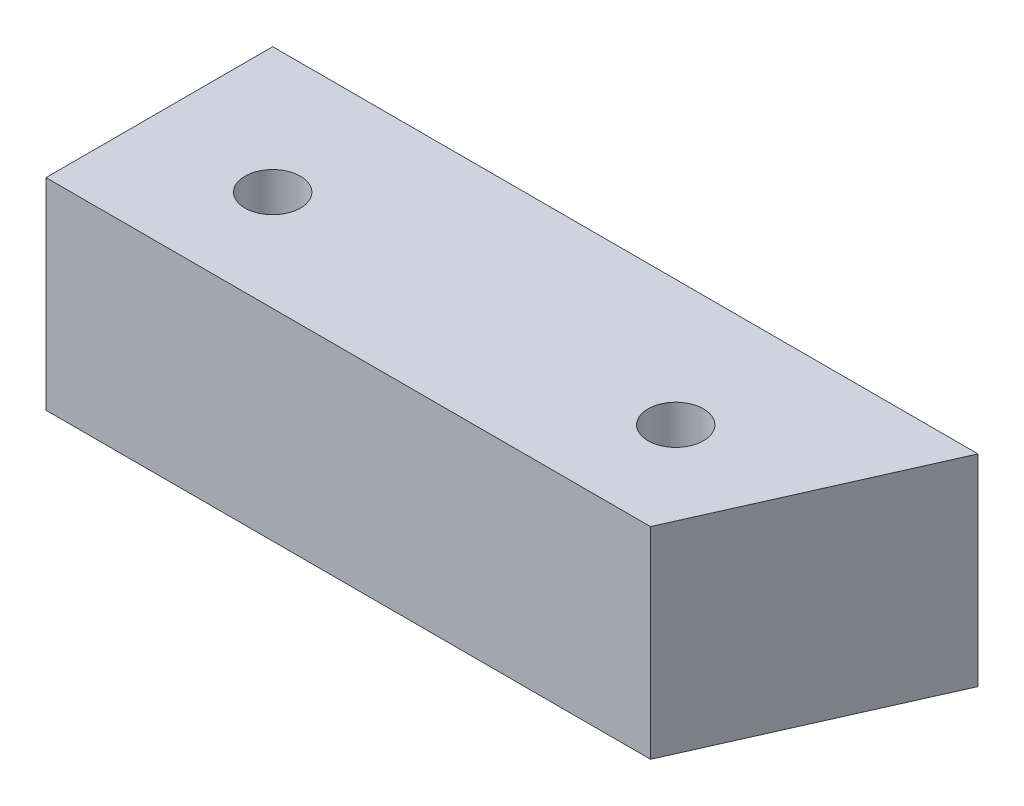
SolidWorks part; units mm, degrees
material "PA Type 6"
ref_plane "Front Plane" through (0, 0, 0) normal (0, 0, 1) x (1, 0, 0)
ref_plane "Top Plane" through (0, 0, 0) normal (0, 1, 0) x (1, 0, 0)
ref_plane "Right Plane" through (0, 0, 0) normal (1, 0, 0) x (0, 0, -1)
sketch "Sketch1" plane through (0, 0, 0) normal (0, 0, 1) x (1, 0, 0)
  line L1 (0, 0) -> (140, 0)
  line L2 (0, 0) -> (0, 40)
  line L3 (0, 40) -> (140, 40)
  line L4 (140, 0) -> (140, 40)
  dimension "D1" = 140
  dimension "D2" = 40
extrude "Boss-Extrude1" add sketch "Sketch1" along normal blind 45
sketch "Sketch2" plane through (0, 0, 0) normal (0, -1, 0) x (1, 0, 0)
  line L0 (120, 45) -> (140, 45)
  line L1 (0, 45) -> (140, 45) construction
  line L2 (140, 45) -> (140, 0)
  line L3 (140, 0) -> (120, 45)
  line L4 (0, 45) -> (0, 0) construction
  circle A0 centre (25, 25) radius 5.5
  circle A1 centre (105, 25) radius 5.5
  dimension "D2" = 11
  dimension "D3" = 11
  dimension "D4" = 20
  dimension "D5" = 20
  dimension "D6" = 80
  dimension "D7" = 35
  dimension "D8" = 25
  dimension "D1" = 20
extrude "Cut-Extrude1" cut sketch "Sketch2" against normal through all
sketch "Sketch3" plane through (0, 0, 0) normal (0, 0, -1) x (-1, 0, 0)
  line L0 (0, 40) -> (0, 0) construction
  line L1 (-140, 40) -> (0, 40) construction
  line L2 (0, 0) -> (-140, 0) construction
  circle A0 centre (-40, 25) radius 2.5
  circle A1 centre (-100, 25) radius 2.5
  circle A2 centre (-40, 15) radius 2.5
  circle A3 centre (-100, 15) radius 2.5
  dimension "D1" = 40
  dimension "D2" = 60
  dimension "D3" = 40
  dimension "D4" = 60
  dimension "D5" = 5
  dimension "D6" = 15
  dimension "D7" = 15
  dimension "D8" = 15
  dimension "D9" = 15
extrude "Cut-Extrude2" cut sketch "Sketch3" against normal blind 20
